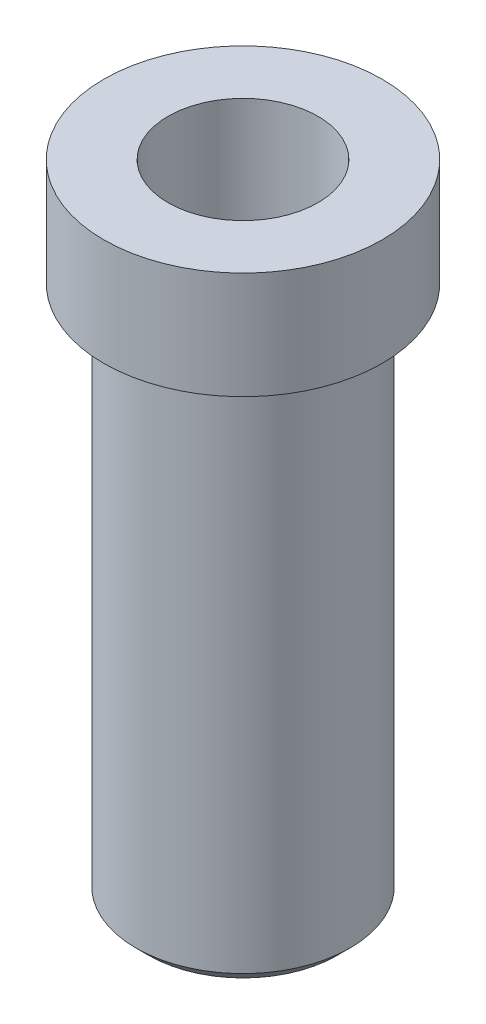
SolidWorks part; units mm, degrees
ref_plane "Front Plane" through (0, 0, 0) normal (0, 0, 1) x (1, 0, 0)
ref_plane "Top Plane" through (0, 0, 0) normal (0, 1, 0) x (1, 0, 0)
ref_plane "Right Plane" through (0, 0, 0) normal (1, 0, 0) x (0, 0, -1)
sketch "Sketch1" plane through (0, 0, 0) normal (0, 0, 1) x (1, 0, 0)
  line L0 (0, 1.5298) -> (0, -1.4702) construction
  line L1 (-0.9899, 0) -> (0.7867, 0) construction
  line L2 (0.65, 1.5298) -> (0.35, 1.5298)
  line L3 (0.35, 1.5298) -> (0.35, -1.4702)
  line L4 (0.35, -1.4702) -> (0.5, -1.4702)
  line L5 (0.5, -1.4702) -> (0.5, 1.0298)
  line L6 (0.5, 1.0298) -> (0.65, 1.0298)
  line L7 (0.65, 1.0298) -> (0.65, 1.5298)
  point P7 (-5.4444, 2.0407)
  point P12 (-3.4282, 0.1619)
  point P13 (0.45, 1.5298)
  dimension "D1" = 3
  dimension "D2" = 2.5
  dimension "D3" = 0.5
  dimension "D5" = 0.7
  dimension "D6" = 1
  dimension "D7" = 0.3
revolve "Revolve1" add sketch "Sketch1" angle 360 about L0
chamfer "Chamfer1" distance 0.06 angle 45 1 edges at (0, -1.4702, 0.5)
